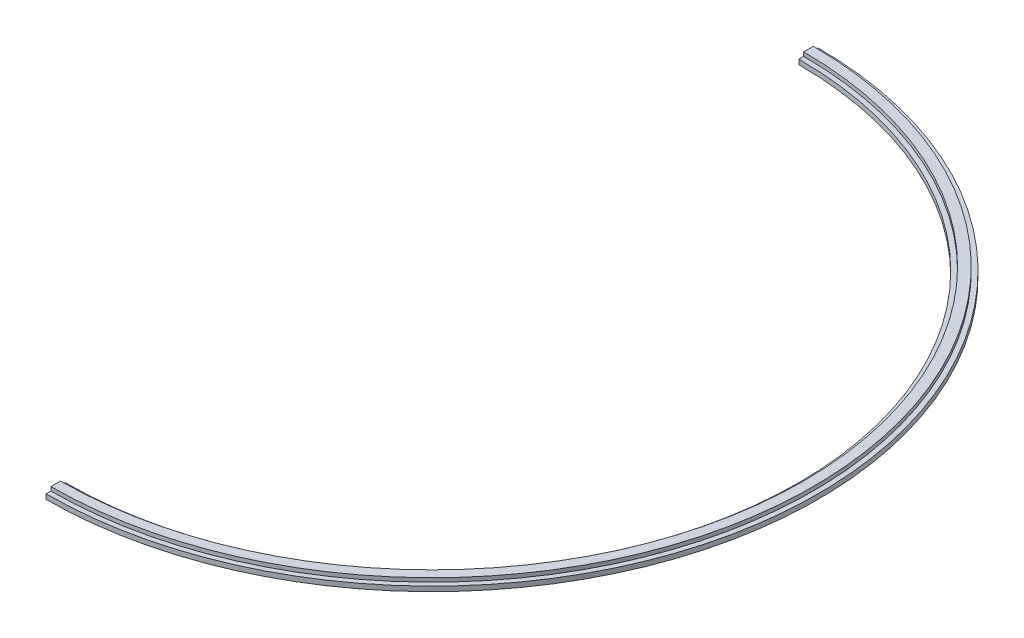
SolidWorks part; units mm, degrees
ref_plane "Front Plane" through (0, 0, 0) normal (0, 0, 1) x (1, 0, 0)
ref_plane "Top Plane" through (0, 0, 0) normal (0, 1, 0) x (1, 0, 0)
ref_plane "Right Plane" through (0, 0, 0) normal (1, 0, 0) x (0, 0, -1)
sketch "Sketch1" plane through (0, 0, 0) normal (0, 1, 0) x (1, 0, 0)
  line L0 (0, 4000) -> (0, -4000)
  circle A0 centre (0, 0) radius 4000
  circle A1 centre (0, 0) radius 3800
  dimension "D1" = 8000
  dimension "D2" = 7600
extrude "Boss-Extrude1" add sketch "Sketch1" along normal blind 50 contours A1 L0 A0
sketch "Sketch2" plane through (0, 50, 0) normal (0, 1, 0) x (1, 0, 0)
  line L0 (0, 3950) -> (0, -3950)
  circle A0 centre (0, 0) radius 3950
  circle A1 centre (0, 0) radius 3850
  line M4 (0, 4000) -> (0, 3800)
  dimension "D1" = 7900
  dimension "D2" = 7700
extrude "Boss-Extrude2" add sketch "Sketch2" along normal blind 40 contours A1 L0 A0 M4
